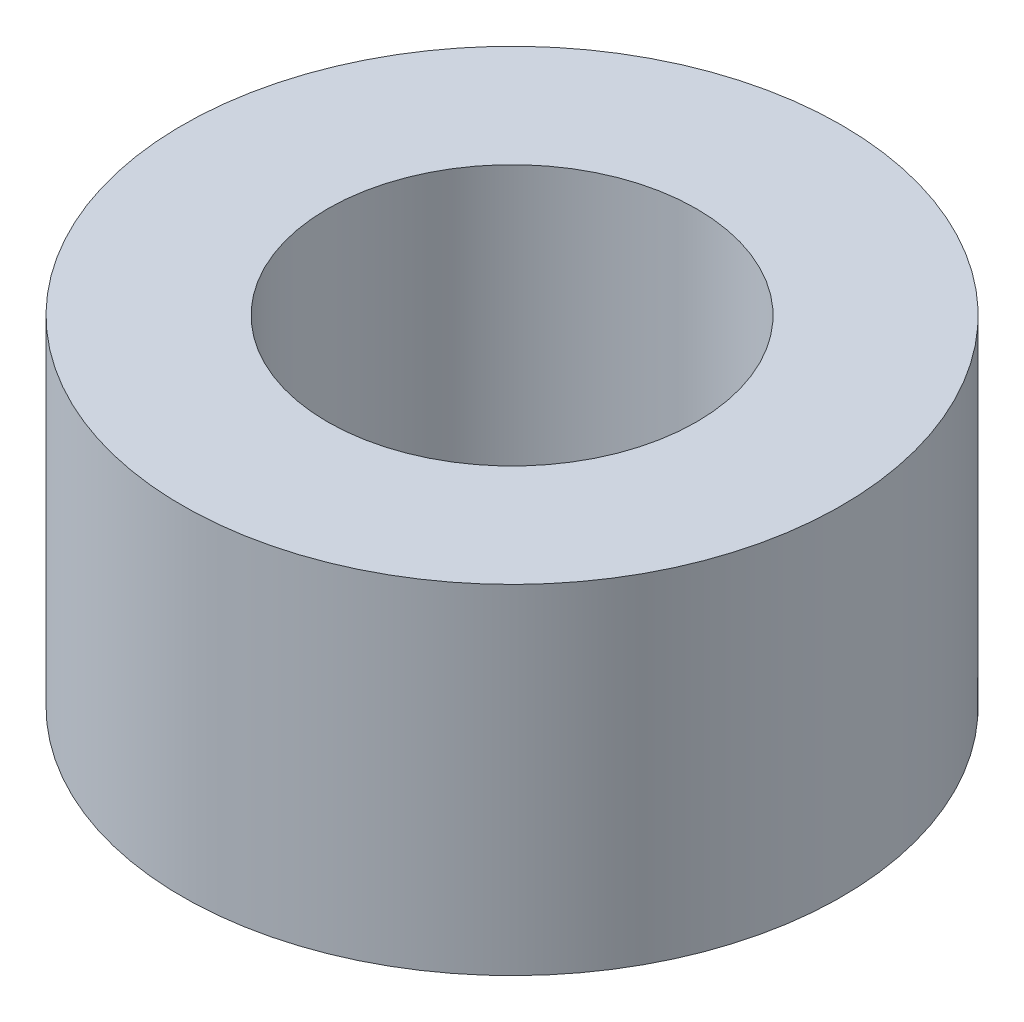
SolidWorks part; units mm, degrees
material "ABS"
ref_plane "Front Plane" through (0, 0, 0) normal (0, 0, 1) x (1, 0, 0)
ref_plane "Top Plane" through (0, 0, 0) normal (0, 1, 0) x (1, 0, 0)
ref_plane "Right Plane" through (0, 0, 0) normal (1, 0, 0) x (0, 0, -1)
sketch "Sketch1" plane through (0, 0, 0) normal (0, 1, 0) x (1, 0, 0)
  circle A0 centre (0, 0) radius 3.175
  circle A1 centre (0, 0) radius 1.778
  dimension "D1" = 3.556
  dimension "D2" = 6.35
extrude "Boss-Extrude1" add sketch "Sketch1" along normal blind 3.2639
